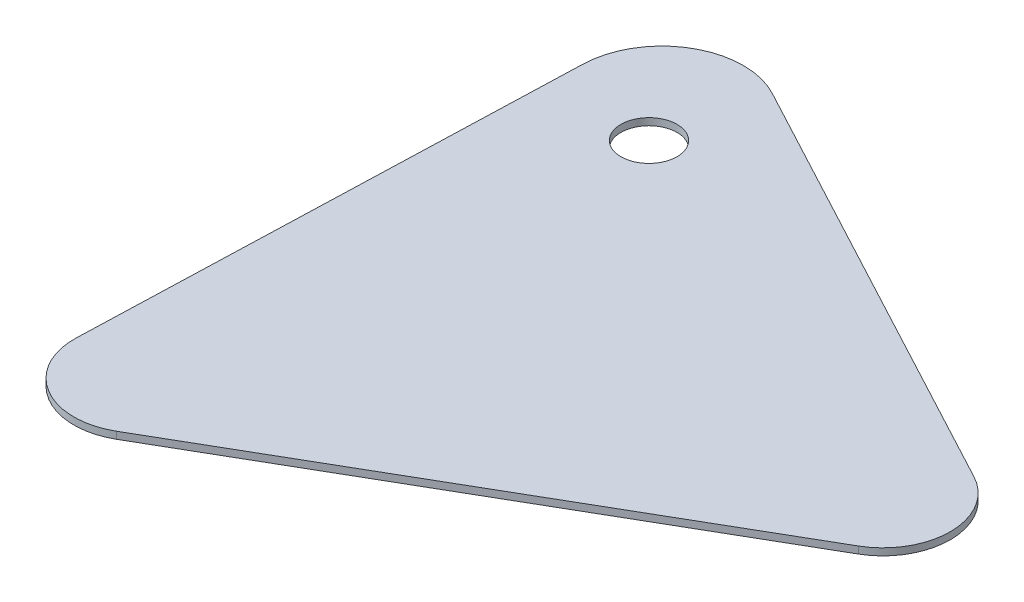
SolidWorks part; units mm, degrees
material "AISI 4130 Steel, annealed at 865C"
ref_plane "Front Plane" through (0, 0, 0) normal (0, 0, 1) x (1, 0, 0)
ref_plane "Top Plane" through (0, 0, 0) normal (0, 1, 0) x (1, 0, 0)
ref_plane "Right Plane" through (0, 0, 0) normal (1, 0, 0) x (0, 0, -1)
sketch "Sketch1" plane through (0, 0, 0) normal (0, 1, 0) x (1, 0, 0)
  line L1 (211.5344, 68.3119) -> (-33.0276, 198.9094)
  line L2 (-87.244, 167.6076) -> (-96.4242, -109.4881)
  line L3 (-96.4242, -109.4881) -> (211.5344, 68.3119)
  arc A3 (-33.0276, 198.9094) -> (-87.244, 167.6076) centre (-50.3949, 166.3868) ccw
  point P8 (-96.4242, -109.4881)
  point P13 (-85.2825, 226.8139)
  dimension "D2" = 355.6
  dimension "D1" = 215.9
extrude "Boss-Extrude1" add sketch "Sketch1" along normal blind 3.175
sketch "Sketch2" plane through (0, 3.175, 0) normal (0, 1, 0) x (1, 0, 0)
  line L0 (-87.244, 167.6076) -> (-33.0276, 198.9094) construction
  line L1 (-87.244, 167.6076) -> (-96.4242, -109.4881) construction
  line L2 (-60.1358, 183.2585) -> (-42.3558, 152.4626) construction
  circle A0 centre (-42.3558, 152.4626) radius 12.7
  arc A2 (-33.0276, 198.9094) -> (-87.244, 167.6076) centre (-50.3949, 166.3868) ccw construction
  dimension "D1" = 25.4
  dimension "D2" = 35.56
extrude "Cut-Extrude1" cut sketch "Sketch2" against normal blind 76.2
fillet "Fillet1" radius 30.48 2 edges at (211.5344, 1.5875, -68.3119) (-96.4242, 1.5875, 109.4881)
